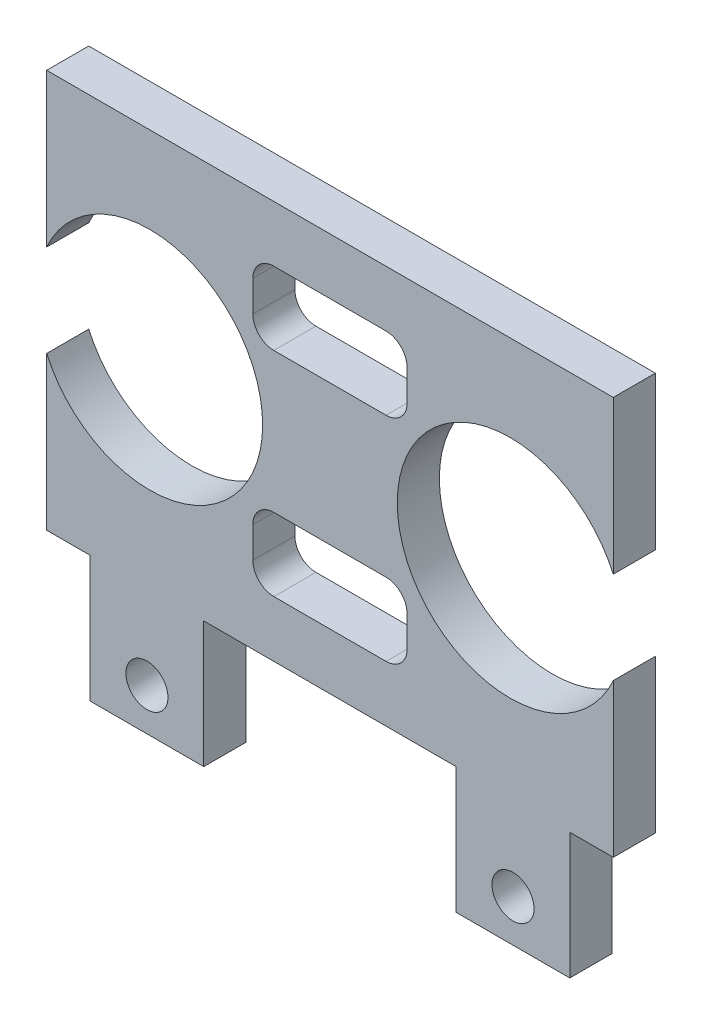
SolidWorks part; units mm, degrees
ref_plane "Plano frontal" through (0, 0, 0) normal (0, 0, 1) x (1, 0, 0)
ref_plane "Plano superior" through (0, 0, 0) normal (0, 1, 0) x (1, 0, 0)
ref_plane "Plano direito" through (0, 0, 0) normal (1, 0, 0) x (0, 0, -1)
sketch "Esboço1" plane through (0, 0, 0) normal (0, 0, 1) x (1, 0, 0)
  line L0 (0, 14.2) -> (40.4, 14.2) construction
  line L1 (0, 0) -> (3.1, 0)
  line L2 (0, 0) -> (0, 28.4)
  line L3 (0, 28.4) -> (40.4, 28.4)
  line L4 (40.4, 0) -> (40.4, 28.4)
  line L5 (20.2, 28.4) -> (20.2, -2.344) construction
  line L6 (11.2, 0) -> (29.2, 0)
  line L8 (3.1, 0) -> (3.1, -9)
  line L9 (3.1, -9) -> (11.2, -9)
  line L10 (11.2, 0) -> (11.2, -9)
  line L11 (37.3, -9) -> (29.2, -9)
  line L12 (29.2, 0) -> (29.2, -9)
  line L13 (37.3, 0) -> (37.3, -9)
  line L14 (37.3, 0) -> (40.4, 0)
  line L15 (14.7, 24.4) -> (14.7, 19.2)
  line L16 (25.7, 19.2) -> (14.7, 19.2)
  line L18 (25.7, 24.4) -> (14.7, 24.4)
  line L20 (25.7, 24.4) -> (25.7, 19.2)
  line L21 (25.7, 4) -> (14.7, 4)
  line L22 (14.7, 4) -> (14.7, 9.2)
  line L23 (25.7, 9.2) -> (14.7, 9.2)
  line L24 (25.7, 4) -> (25.7, 9.2)
  circle A0 centre (7.15, -6) radius 1.5
  circle A1 centre (33.25, -6) radius 1.5
  circle A2 centre (7.35, 14.2) radius 8.05
  circle A5 centre (33.05, 14.2) radius 8.05
  point P23 (20.2, 21.65)
  dimension "D6" = 3
  dimension "D8" = 6
  dimension "D9" = 16.1
  dimension "D10" = 12.85
  dimension "D1" = 40.4
  dimension "D2" = 28.4
  dimension "D3" = 9
  dimension "D4" = 8.1
  dimension "D5" = 18
  dimension "D7" = 4.05
  dimension "D11" = 5
  dimension "D12" = 4
  dimension "D13" = 11
  dimension "D14" = 5.5
extrude "Ressalto-extrusão1" add sketch "Esboço1" along normal blind 3 contours L4 A5 L3 L2 A2 L1 L8 L9 L10 L6 L12 L11 L13 L14 L20 L16 L15 L18 A0 A1
fillet "Filete1" radius 1.5 4 edges at (14.7, 19.2, 1.5) (25.7, 19.2, 1.5) (25.7, 24.4, 1.5) (14.7, 24.4, 1.5)
fillet "Filete2" radius 1.5 4 edges at (14.7, 4, 1.5) (25.7, 4, 1.5) (25.7, 9.2, 1.5) (14.7, 9.2, 1.5)
